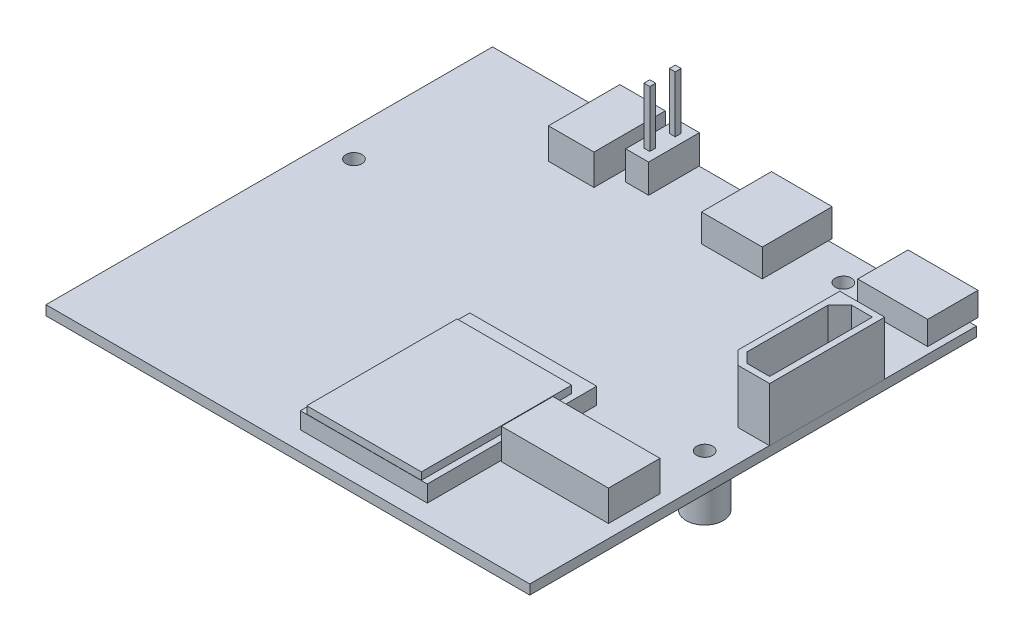
SolidWorks part; units mm, degrees
material "OBC"
ref_plane "Front Plane" through (0, 0, 0) normal (0, 0, 1) x (1, 0, 0)
ref_plane "Top Plane" through (0, 0, 0) normal (0, 1, 0) x (1, 0, 0)
ref_plane "Right Plane" through (0, 0, 0) normal (1, 0, 0) x (0, 0, -1)
sketch "Sketch1" plane through (0, 0, 0) normal (0, 1, 0) x (1, 0, 0)
  line L1 (0, 0) -> (52, 0)
  line L2 (0, 0) -> (0, 48)
  line L3 (0, 48) -> (52, 48)
  line L4 (52, 0) -> (52, 48)
  dimension "D1" = 52
  dimension "D2" = 48
extrude "Base" add sketch "Sketch1" along normal blind 1.04
sketch "Sketch8" plane through (0, 1.04, 0) normal (0, 1, 0) x (1, 0, 0)
  line L1 (13.6525, 48.0254) -> (18.542, 48.0254)
  line L2 (13.6525, 48.0254) -> (13.6525, 40.3546)
  line L3 (13.6525, 40.3546) -> (18.542, 40.3546)
  line L4 (18.542, 48.0254) -> (18.542, 40.3546)
  line L5 (0, 48) -> (0, 0) construction
  line L7 (52, 48) -> (0, 48) construction
  dimension "D1" = 7.6708
  dimension "D2" = 4.8895
  dimension "D3" = 18.542
  dimension "D4" = 0.0254
extrude "DC power" add sketch "Sketch8" along normal blind 3.302
sketch "Sketch9" plane through (0, 0, -48.0254) normal (0, 0, -1) x (-1, 0, 0)
  line L0 (-17.3472, 2.3154) -> (-18.542, 2.3154) construction
  line L1 (-18.542, 4.342) -> (-18.542, 1.04) construction
  line L2 (-14.8472, 2.3154) -> (-13.6525, 2.3154) construction
  line L3 (-13.6525, 4.342) -> (-13.6525, 1.04) construction
  line L4 (-18.542, 1.0654) -> (-13.6525, 1.0654) construction
  line L5 (-18.542, 1.04) -> (-13.6525, 1.04) construction
  line L6 (-13.6525, 4.342) -> (-13.6525, 1.04) construction
  line L7 (-18.542, 4.342) -> (-18.542, 1.04) construction
  circle A0 centre (-16.0972, 2.3154) radius 1.25
  dimension "D1" = 2.5
  dimension "D2" = 0.0254
extrude "DC power hole" cut sketch "Sketch9" against normal blind 5.842
sketch "Sketch10" plane through (0, 0, -42.1834) normal (0, 0, -1) x (-1, 0, 0)
  circle A0 centre (-16.0972, 2.3154) radius 0.4
  circle A2 centre (-16.0972, 2.3154) radius 1.25 construction
  dimension "D1" = 0.8
extrude "DC power pin" add sketch "Sketch10" along normal blind 4.1656
sketch "Sketch11" plane through (0, 1.04, 0) normal (0, 1, 0) x (1, 0, 0)
  line L0 (52, 48) -> (18.542, 48) construction
  line L1 (22.2058, 42.5644) -> (19.742, 42.5644)
  line L2 (22.2058, 42.5644) -> (22.2058, 48.0254)
  line L3 (22.2058, 48.0254) -> (19.742, 48.0254)
  line L4 (19.742, 42.5644) -> (19.742, 48.0254)
  line L5 (52, 0) -> (52, 48) construction
  dimension "D1" = 0.0254
  dimension "D2" = 2.4638
  dimension "D3" = 5.461
  dimension "D4" = 32.258
extrude "PWM pin base" add sketch "Sketch11" along normal blind 3.0988
sketch "Sketch12" plane through (0, 4.1388, 0) normal (0, 1, 0) x (1, 0, 0)
  line L0 (22.2058, 45.2949) -> (19.742, 45.2949) construction
  line L1 (21.2914, 43.6121) -> (20.6564, 43.6121)
  line L2 (21.2914, 43.6121) -> (21.2914, 44.2471)
  line L3 (21.2914, 44.2471) -> (20.6564, 44.2471)
  line L4 (20.6564, 43.6121) -> (20.6564, 44.2471)
  line L5 (22.2058, 42.5644) -> (22.2058, 48.0254) construction
  line L6 (19.742, 48.0254) -> (19.742, 42.5644) construction
  line L7 (20.9739, 42.5644) -> (20.9739, 48.0254) construction
  line L8 (19.742, 42.5644) -> (22.2058, 42.5644) construction
  line L9 (22.2058, 48.0254) -> (19.742, 48.0254) construction
  line L10 (20.9739, 43.6121) -> (20.9739, 44.2471) construction
  line L11 (21.1837, 42.5644) -> (21.1837, 43.6121) construction
  line L12 (21.2914, 46.9776) -> (21.2914, 46.3426)
  line L13 (21.1837, 44.2471) -> (21.1837, 45.2949) construction
  line L14 (21.2914, 46.3426) -> (20.6564, 46.3426)
  line L15 (21.2914, 46.9776) -> (20.6564, 46.9776)
  line L16 (20.6564, 46.9776) -> (20.6564, 46.3426)
  dimension "D1" = 0.635
  dimension "D2" = 0.635
extrude "PWM pins" add sketch "Sketch12" along normal blind 6.0452
sketch "Sketch13" plane through (0, 1.04, 0) normal (0, 1, 0) x (1, 0, 0)
  line L0 (52, 48) -> (22.2058, 48) construction
  line L1 (36.0996, 40.888) -> (29.5718, 40.888)
  line L2 (36.0996, 40.888) -> (36.0996, 48.4064)
  line L3 (36.0996, 48.4064) -> (29.5718, 48.4064)
  line L4 (29.5718, 40.888) -> (29.5718, 48.4064)
  line L5 (52, 0) -> (52, 48) construction
  dimension "D1" = 6.5278
  dimension "D2" = 0.4064
  dimension "D3" = 7.5184
  dimension "D4" = 22.4282
extrude "Micro HDMI port" add sketch "Sketch13" along normal blind 2.9718
sketch "Sketch14" plane through (0, 1.04, 0) normal (0, 1, 0) x (1, 0, 0)
  line L0 (52, 48) -> (36.0996, 48) construction
  line L1 (51.2888, 43.4788) -> (43.7704, 43.4788)
  line L2 (51.2888, 43.4788) -> (51.2888, 48.889)
  line L3 (51.2888, 48.889) -> (43.7704, 48.889)
  line L4 (43.7704, 43.4788) -> (43.7704, 48.889)
  line L5 (52, 0) -> (52, 48) construction
  dimension "D1" = 7.5184
  dimension "D2" = 5.4102
  dimension "D3" = 0.889
  dimension "D4" = 8.2296
extrude "Micro USB port" add sketch "Sketch14" along normal blind 2.54
sketch "Sketch15" plane through (0, 0, 0) normal (0, -1, 0) x (-1, 0, 0)
  line L0 (0, 0) -> (-52, 0) construction
  line L1 (0, 48) -> (0, 0) construction
  line L2 (-40.8, 45.7648) -> (-44.7677, 45.7648) construction
  line L3 (-52, 48) -> (0, 48) construction
  circle A0 centre (-3, 30.1) radius 0.8636
  circle A1 centre (-49, 21.8012) radius 0.8636
  circle A2 centre (-40.8, 44.9012) radius 0.8636
  dimension "D1" = 30.1
  dimension "D2" = 3
  dimension "D3" = 1.7272
  dimension "D5" = 37.8
  dimension "D6" = 23.1
  dimension "D7" = 2.2352
  dimension "D4" = 49
extrude "Header hole" cut sketch "Sketch15" against normal up to next
sketch "Sketch16" plane through (0, 0, 0) normal (0, -1, 0) x (1, 0, 0)
  circle A0 centre (49, -21.8012) radius 1.9939
  circle A2 centre (3, -30.1) radius 1.9939
  circle A3 centre (49, -21.8012) radius 0.8636 construction
  circle A5 centre (3, -30.1) radius 0.8636 construction
  dimension "D1" = 3.9878
extrude "Standoffs 1" add sketch "Sketch16" along normal blind 4.4704
sketch "Sketch17" plane through (0, 0, 0) normal (0, -1, 0) x (1, 0, 0)
  circle A0 centre (40.8, -44.9012) radius 1.9939
  circle A1 centre (40.8, -44.9012) radius 0.8636 construction
  circle A2 centre (49, -21.8012) radius 1.9939 construction
extrude "Short standoff" add sketch "Sketch17" along normal blind 4.4704
sketch "Sketch19" plane through (0, 0, 0) normal (0, -1, 0) x (1, 0, 0)
  circle A1 centre (40.8, -44.9012) radius 0.8636
  circle A2 centre (40.8, -44.9012) radius 0.8636
  circle A3 centre (49, -21.8012) radius 0.8636
  circle A4 centre (49, -21.8012) radius 0.8636
  circle A5 centre (3, -30.1) radius 0.8636
  circle A6 centre (3, -30.1) radius 0.8636
  dimension "D1" = 0
  dimension "D2" = 0
  dimension "D3" = 0
extrude "Threads in standoffs" cut sketch "Sketch19" along normal up to next
sketch "Sketch20" plane through (0, 0, 0) normal (0, -1, 0) x (-1, 0, 0)
  line L0 (-52, 0) -> (-52, 48) construction
  line L1 (-43.872, 25.14) -> (-31.7562, 25.14)
  line L2 (-43.872, 25.14) -> (-43.872, 37.2558)
  line L3 (-43.872, 37.2558) -> (-31.7562, 37.2558)
  line L4 (-31.7562, 25.14) -> (-31.7562, 37.2558)
  line L5 (-52, 48) -> (0, 48) construction
  dimension "D1" = 12.1158
  dimension "D2" = 12.1158
  dimension "D3" = 20.2438
  dimension "D4" = 22.86
extrude "CPU" add sketch "Sketch20" along normal blind 1.4732
sketch "Sketch21" plane through (0, 1.04, 0) normal (0, 1, 0) x (1, 0, 0)
  line L0 (52, 0) -> (52, 48) construction
  line L1 (52.0254, 38.1254) -> (47.1994, 38.1254)
  line L2 (52.0254, 38.1254) -> (52.0254, 25.7556)
  line L3 (52.0254, 25.7556) -> (48.6362, 25.7556)
  line L4 (47.1994, 38.1254) -> (47.1994, 27.1924)
  line L5 (0, 0) -> (52, 0) construction
  line L6 (47.1994, 27.1924) -> (48.6362, 25.7556)
  dimension "D1" = 0.0254
  dimension "D2" = 12.3698
  dimension "D3" = 4.826
  dimension "D4" = 38.1254
  dimension "D5" = 2.032
  dimension "D6" = 45
extrude "UART plastic" add sketch "Sketch21" along normal blind 5.7912
sketch "Sketch22" plane through (0, 6.8312, 0) normal (0, 1, 0) x (1, 0, 0)
  line L0 (51.365, 37.465) -> (49.135, 37.465)
  line L1 (47.8598, 36.1898) -> (47.8598, 27.466)
  line L2 (47.8598, 27.466) -> (48.9098, 26.416)
  line L3 (48.9098, 26.416) -> (51.365, 26.416)
  line L4 (51.365, 26.416) -> (51.365, 37.465)
  line L5 (52.0254, 38.1254) -> (47.1994, 38.1254)
  line L6 (47.1994, 38.1254) -> (47.1994, 27.1924)
  line L7 (47.1994, 27.1924) -> (48.6362, 25.7556)
  line L8 (48.6362, 25.7556) -> (52.0254, 25.7556)
  line L9 (52.0254, 25.7556) -> (52.0254, 38.1254)
  line L10 (52.0254, 38.1254) -> (47.1994, 38.1254) construction
  line L11 (47.1994, 38.1254) -> (47.1994, 27.1924) construction
  line L12 (47.1994, 27.1924) -> (48.6362, 25.7556) construction
  line L13 (48.6362, 25.7556) -> (52.0254, 25.7556) construction
  line L14 (52.0254, 25.7556) -> (52.0254, 38.1254) construction
  line L15 (47.8598, 36.1898) -> (49.135, 37.465)
  line L17 (51.365, 37.465) -> (47.8598, 37.465) construction
  line L18 (47.8598, 37.465) -> (47.8598, 27.466) construction
  dimension "D3" = 45
  dimension "D4" = 1.8034
  dimension "D1" = 0
  dimension "D2" = 0.6604
extrude "UART hole" cut sketch "Sketch22" against normal blind 4.1656
sketch "Sketch23" plane through (0, 1.04, 0) normal (0, 1, 0) x (1, 0, 0)
  line L0 (52, 0) -> (52, 25.7556) construction
  line L1 (39.0968, 15.3924) -> (50.603, 15.3924)
  line L2 (39.0968, 15.3924) -> (39.0968, 9.8552)
  line L3 (39.0968, 9.8552) -> (50.603, 9.8552)
  line L4 (50.603, 15.3924) -> (50.603, 9.8552)
  line L5 (0, 0) -> (52, 0) construction
  dimension "D1" = 11.5062
  dimension "D2" = 5.5372
  dimension "D3" = 12.9032
  dimension "D4" = 15.3924
extrude "MicroSD" add sketch "Sketch23" along normal blind 3.302
sketch "Sketch24" plane through (0, 1.04, 0) normal (0, 1, 0) x (1, 0, 0)
  line L0 (0, 0) -> (52, 0) construction
  line L1 (25.3238, 20.2311) -> (38.9636, 20.2311)
  line L2 (25.3238, 20.2311) -> (25.3238, 2.0193)
  line L3 (25.3238, 2.0193) -> (38.9636, 2.0193)
  line L4 (38.9636, 20.2311) -> (38.9636, 2.0193)
  dimension "D1" = 18.2118
  dimension "D2" = 13.6398
  dimension "D3" = 20.2311
extrude "eMMC board" add sketch "Sketch24" along normal blind 1.778
sketch "Sketch25" plane through (0, 2.818, 0) normal (0, 1, 0) x (1, 0, 0)
  line L0 (25.3238, 2.0193) -> (38.9636, 2.0193) construction
  line L1 (25.9842, 18.1991) -> (38.3032, 18.1991)
  line L2 (25.9842, 18.1991) -> (25.9842, 2.0447)
  line L3 (25.9842, 2.0447) -> (38.3032, 2.0447)
  line L4 (38.3032, 18.1991) -> (38.3032, 2.0447)
  line L5 (38.9636, 2.0193) -> (38.9636, 20.2311) construction
  line L6 (25.3238, 15.3001) -> (25.9842, 15.3001) construction
  line L7 (25.3238, 20.2311) -> (25.3238, 2.0193) construction
  line L9 (38.3032, 15.3001) -> (38.9636, 15.3001) construction
  dimension "D1" = 0.0254
  dimension "D2" = 16.1544
  dimension "D3" = 12.9794
extrude "eMMC chip" add sketch "Sketch25" along normal blind 0.7874
